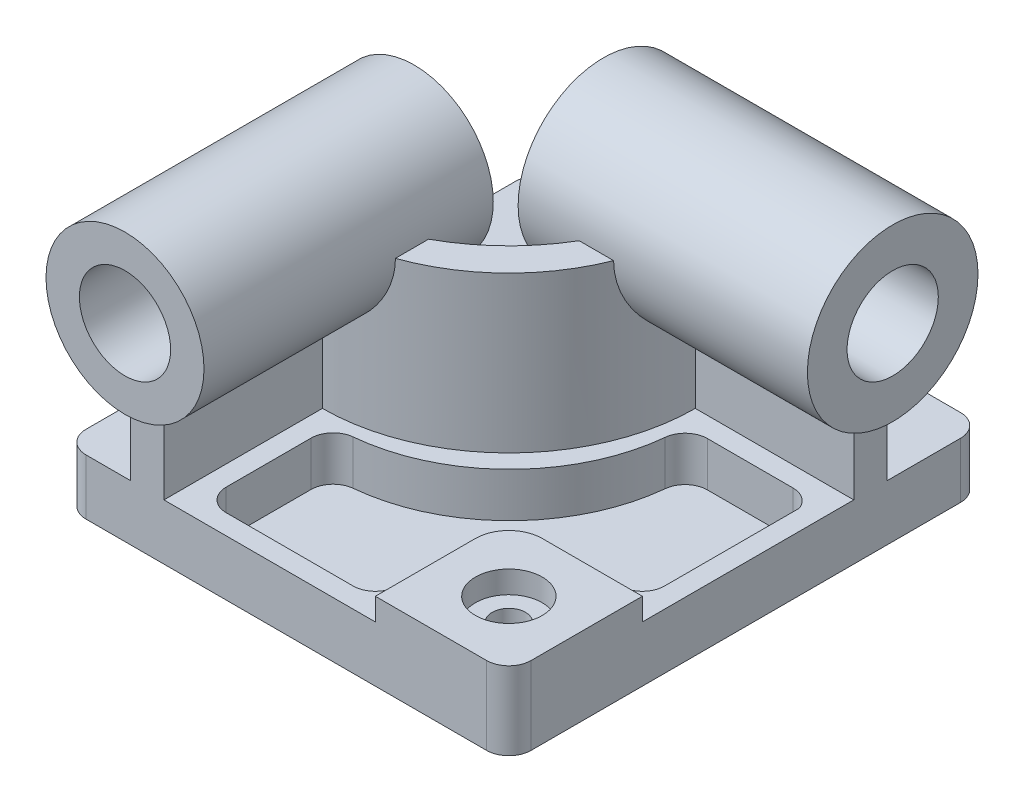
SolidWorks part; units mm, degrees
ref_plane "Front Plane" through (0, 0, 0) normal (0, 0, 1) x (1, 0, 0)
ref_plane "Top Plane" through (0, 0, 0) normal (0, 1, 0) x (1, 0, 0)
ref_plane "Right Plane" through (0, 0, 0) normal (1, 0, 0) x (0, 0, -1)
sketch "Sketch1" plane through (0, 0, 0) normal (0, 1, 0) x (1, 0, 0)
  line L1 (0, 0) -> (200, 0)
  line L2 (0, 0) -> (0, -213)
  line L3 (0, -213) -> (200, -213)
  line L4 (200, 0) -> (200, -213)
  dimension "D1" = 213
  dimension "D2" = 200
extrude "Boss-Extrude1" add sketch "Sketch1" along normal blind 25
sketch "Sketch2" plane through (0, 25, 0) normal (0, 1, 0) x (1, 0, 0)
  line L1 (200, -213) -> (140, -213)
  line L2 (200, -213) -> (200, -153)
  line L3 (200, -153) -> (140, -153)
  line L4 (140, -213) -> (140, -153)
  dimension "D1" = 60
  dimension "D2" = 60
extrude "Boss-Extrude2" add sketch "Sketch2" along normal blind 10
sketch "Sketch3" plane through (0, 25, 0) normal (0, 1, 0) x (1, 0, 0)
  line L0 (30, -213) -> (30, -133)
  line L1 (0, -213) -> (140, -213) construction
  line L2 (120, -43) -> (200, -43)
  line L3 (200, -153) -> (200, 0) construction
  line L4 (45, -213) -> (45, -141.7868)
  line L5 (128.7868, -58) -> (200, -58)
  line L6 (30, -213) -> (45, -213)
  line L7 (200, -43) -> (200, -58)
  arc A0 (30, -133) -> (120, -43) centre (30, -43) ccw
  arc A1 (45, -141.7868) -> (128.7868, -58) centre (45, -58) ccw
  dimension "D6" = 15
  dimension "D1" = 80
  dimension "D2" = 80
  dimension "D3" = 170
  dimension "D4" = 15
  dimension "D5" = 15
sketch "Sketch5" plane through (0, 25, 0) normal (0, 1, 0) x (1, 0, 0)
  line L0 (191, -73.4002) -> (191, -134)
  line L1 (181, -144) -> (145.5248, -144)
  line L2 (131, -158.5248) -> (131, -194)
  line L3 (121, -204) -> (64, -204)
  line L4 (54, -194) -> (54, -155.9255)
  line L5 (143.2203, -67) -> (181.6704, -67)
  line L6 (200, -153) -> (200, 0) construction
  line L7 (200, -153) -> (140, -153) construction
  line L8 (140, -153) -> (140, -213) construction
  line L9 (0, -213) -> (140, -213) construction
  line L10 (128.7868, -58) -> (200, -58) construction
  line L11 (45, -213) -> (45, -141.7868) construction
  arc A0 (191, -134) -> (181, -144) centre (181, -134) cw
  arc A1 (145.5248, -144) -> (131, -158.5248) centre (145.5248, -158.5248) ccw
  arc A2 (131, -194) -> (121, -204) centre (121, -194) cw
  arc A3 (64, -204) -> (54, -194) centre (64, -194) cw
  arc A4 (54, -155.9255) -> (63.0371, -145.9719) centre (64, -155.9255) cw
  arc A5 (63.0371, -145.9719) -> (133.2704, -76) centre (55.5116, -68.1845) ccw
  arc A6 (133.2704, -76) -> (143.2203, -67) centre (143.2203, -77) cw
  arc A7 (181.6704, -67) -> (191, -73.4002) centre (181.6704, -77) cw
  arc A8 (45, -141.7868) -> (128.7868, -58) centre (45, -58) ccw construction
  dimension "D6" = 9
  dimension "D8" = 10
  dimension "D9" = 10
  dimension "D10" = 10
  dimension "D11" = 10
  dimension "D12" = 10
  dimension "D13" = 10
  dimension "D1" = 9
  dimension "D2" = 9
  dimension "D3" = 9
  dimension "D4" = 9
  dimension "D5" = 9
  dimension "D7" = 9
extrude "Cut-Extrude1" cut sketch "Sketch5" against normal blind 20
extrude "Boss-Extrude3" add sketch "Sketch3" along normal blind 70
sketch "Sketch6" plane through (0, 0, 213) normal (0, 0, 1) x (1, 0, 0)
  line L0 (0, 0) -> (200, 0) construction
  line L1 (30, 95) -> (30, 25) construction
  circle A0 centre (37.5, 95) radius 35.5
  point P4 (0, 0)
  dimension "D1" = 71
  dimension "D2" = 95
  dimension "D3" = 7.5
extrude "Boss-Extrude5" add sketch "Sketch6" against normal blind 120 and the other way blind 10
sketch "Sketch7" plane through (200, 0, 0) normal (1, 0, 0) x (0, 0, -1)
  line L0 (-213, 0) -> (0, 0) construction
  line L1 (-43, 95) -> (-43, 25) construction
  circle A0 centre (-50.5, 95) radius 38.3333
  dimension "D1" = 76.6667
  dimension "D2" = 95
  dimension "D3" = 7.5
extrude "Boss-Extrude6" add sketch "Sketch7" against normal blind 120 and the other way blind 10
hole_wizard "Ø12.0 (41) Diameter Hole1" positions "Sketch8" profile "Sketch9" hole size "Ø12.0" standard "ANSI Metric" end condition through all
sketch "Sketch8" plane through (210, 0, 0) normal (1, 0, 0) x (0, 0, -1)
  line L0 (-213, 0) -> (0, 0) construction
  line L1 (-43, 57.4075) -> (-43, 25) construction
  point P1 (-50.5, 95)
  dimension "D1" = 95
  dimension "D2" = 7.5
sketch "Sketch9" plane through (210, 95, 50.5) normal (0, 1, 0) x (0, 0, -1)
  line L0 (0, 0) -> (0, 210)
  line L1 (0, 210) -> (20.5, 210)
  line L2 (20.5, 210) -> (20.5, 0)
  line L5 (20.5, 0) -> (0, 0)
  line L11 (0, -6.35) -> (0, 107.95) construction
  dimension "Thru Hole Dia." = 41
  dimension "Thru Hole Depth" = 210
hole_wizard "Ø12.0mm Dowel Hole1" positions "Sketch10" profile "Sketch11" hole size "Ø12.0" standard "ANSI Metric" end condition through all
sketch "Sketch10" plane through (0, 0, 223) normal (0, 0, 1) x (1, 0, 0)
  point P0 (37.5, 95)
sketch "Sketch11" plane through (37.5, 95, 223) normal (1, 0, 0) x (0, -1, 0)
  line L0 (0, 0) -> (0, 223)
  line L1 (0, 223) -> (20.5, 223)
  line L2 (20.5, 223) -> (20.5, 0)
  line L5 (20.5, 0) -> (0, 0)
  line L11 (0, -6.35) -> (0, 107.95) construction
  dimension "Thru Hole Dia." = 41
  dimension "Thru Hole Depth" = 223
hole_wizard "CBORE for M8 Hex Head Bolt1" positions "Sketch14" profile "Sketch13" counterbore size "M8" standard "BSI" end condition through all
sketch "Sketch14" plane through (0, 35, 0) normal (0, 1, 0) x (1, 0, 0)
  line L0 (140, -213) -> (200, -213) construction
  line L2 (200, -213) -> (200, -153) construction
  point P0 (170, -183)
  point P9 (200, -193.5817)
  point P12 (0, 0)
  dimension "D1" = 30
  dimension "D2" = 30
sketch "Sketch13" plane through (170, 35, 183) normal (1, 0, 0) x (0, 0, 1)
  line L0 (0, 0) -> (0, 35)
  line L1 (0, 35) -> (7.5, 35)
  line L3 (7.5, 35) -> (7.5, 10)
  line L4 (7.5, 10) -> (15, 10)
  line L5 (15, 10) -> (15, 0)
  line L7 (15, 0) -> (0, 0)
  line L11 (0, -6.35) -> (0, 107.95) construction
  dimension "Thru Hole Dia." = 15
  dimension "Thru Hole Depth" = 35
  dimension "C'Bore Dia." = 30
  dimension "C'Bore Depth" = 10
fillet "Fillet1" radius 10 4 edges at (0, 12.5, 0) (200, 12.5, 0) (200, 17.5, 213) (0, 12.5, 213)
fillet "Fillet2" radius 15 1 edges at (140, 30, 153)
